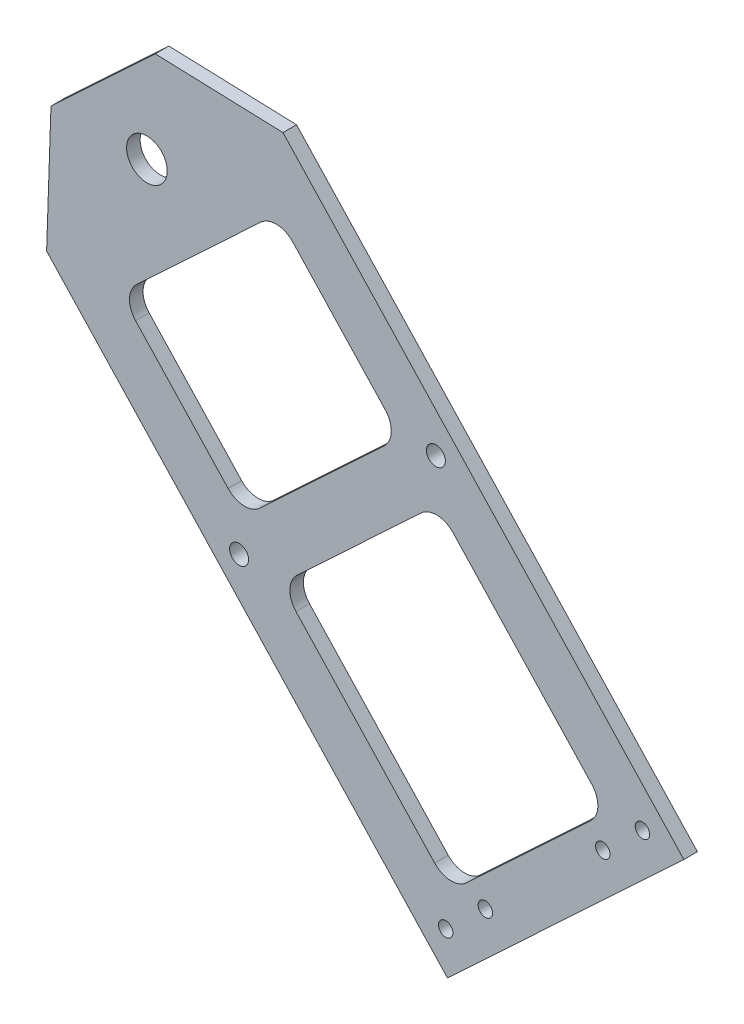
SolidWorks part; units mm, degrees
ref_plane "前视基准面" through (0, 0, 0) normal (0, 0, 1) x (1, 0, 0)
ref_plane "上视基准面" through (0, 0, 0) normal (0, 1, 0) x (1, 0, 0)
ref_plane "右视基准面" through (0, 0, 0) normal (1, 0, 0) x (0, 0, -1)
sketch "草图1" plane through (0, 0, 0) normal (0, 0, 1) x (1, 0, 0)
  line L0 (-324.626, -164.0776) -> (-272.3024, -115.2022)
  line L1 (-324.626, -164.0776) -> (-413.3663, -69.0768)
  line L2 (-272.3024, -115.2022) -> (-361.0428, -20.2014)
  line L3 (-412.4031, -40.8089) -> (-389.3106, -19.2382)
  line L4 (-320.3942, -143.7038) -> (-292.917, -118.0374)
  line L5 (-327.4612, -143.463) -> (-358.179, -110.5781)
  line L6 (-292.6763, -110.9704) -> (-323.3941, -78.0855)
  line L7 (-357.9382, -103.5112) -> (-330.461, -77.8447)
  line L8 (-366.1296, -94.7419) -> (-338.6524, -69.0754)
  line L9 (-373.1966, -94.5011) -> (-393.6751, -72.5778)
  line L10 (-338.4117, -62.0084) -> (-358.8902, -40.0852)
  line L11 (-393.4343, -65.5108) -> (-365.9572, -39.8444)
  line L12 (-413.3663, -69.0768) -> (-412.4031, -40.8089)
  line L13 (-361.0428, -20.2014) -> (-389.3106, -19.2382)
  line L14 (-325.0196, -154.8665) -> (-281.4654, -114.1824) construction
  arc A0 (-292.917, -118.0374) -> (-292.6763, -110.9704) centre (-296.3301, -114.3835) ccw
  arc A1 (-327.4612, -143.463) -> (-320.3942, -143.7038) centre (-323.8073, -140.0499) ccw
  arc A2 (-323.3941, -78.0855) -> (-330.461, -77.8447) centre (-327.0479, -81.4986) ccw
  arc A3 (-358.179, -110.5781) -> (-357.9382, -103.5112) centre (-354.5251, -107.165) cw
  circle A4 centre (-327.2008, -65.2205) radius 2.1 construction
  circle A5 centre (-370.755, -105.9045) radius 2.1 construction
  circle A6 centre (-327.2008, -65.2205) radius 2.1
  circle A7 centre (-370.755, -105.9045) radius 2.1
  arc A8 (-358.8902, -40.0852) -> (-365.9572, -39.8444) centre (-362.5441, -43.4983) ccw
  arc A9 (-338.6524, -69.0754) -> (-338.4117, -62.0084) centre (-342.0655, -65.4215) ccw
  arc A10 (-373.1966, -94.5011) -> (-366.1296, -94.7419) centre (-369.5427, -91.088) ccw
  arc A11 (-393.6751, -72.5778) -> (-393.4343, -65.5108) centre (-390.0212, -69.1647) cw
  circle A12 centre (-391.1637, -40.4006) radius 4.5
  circle A13 centre (-325.0196, -154.8665) radius 1.6
  circle A14 centre (-316.2503, -146.6751) radius 1.6
  circle A15 centre (-290.2347, -122.3739) radius 1.6
  circle A16 centre (-281.4654, -114.1824) radius 1.6
  point P4 (-374.6951, -5.5859)
  point P5 (-427.0187, -54.4613)
  point P20 (-289.2632, -114.6243)
  point P25 (-326.8071, -74.4316)
  point P36 (-362.3033, -36.4313)
  point P39 (-334.9986, -65.6623)
  point P55 (0, 0)
  point P56 (0, 0)
  dimension "D10" = 5
  dimension "D11" = 5
  dimension "D14" = 9
  dimension "D15" = 3.2
  dimension "D19" = 6
  dimension "D20" = 6
  dimension "D1" = 150
  dimension "D2" = 12
  dimension "D3" = 12
  dimension "D4" = 12
  dimension "D5" = 12
  dimension "D6" = 12
  dimension "D7" = 12
  dimension "D8" = 55
  dimension "D9" = 40
  dimension "D16" = 7
  dimension "D17" = 12
  dimension "D18" = 12
extrude "凸台-拉伸1" add sketch "草图1" along normal blind 3
